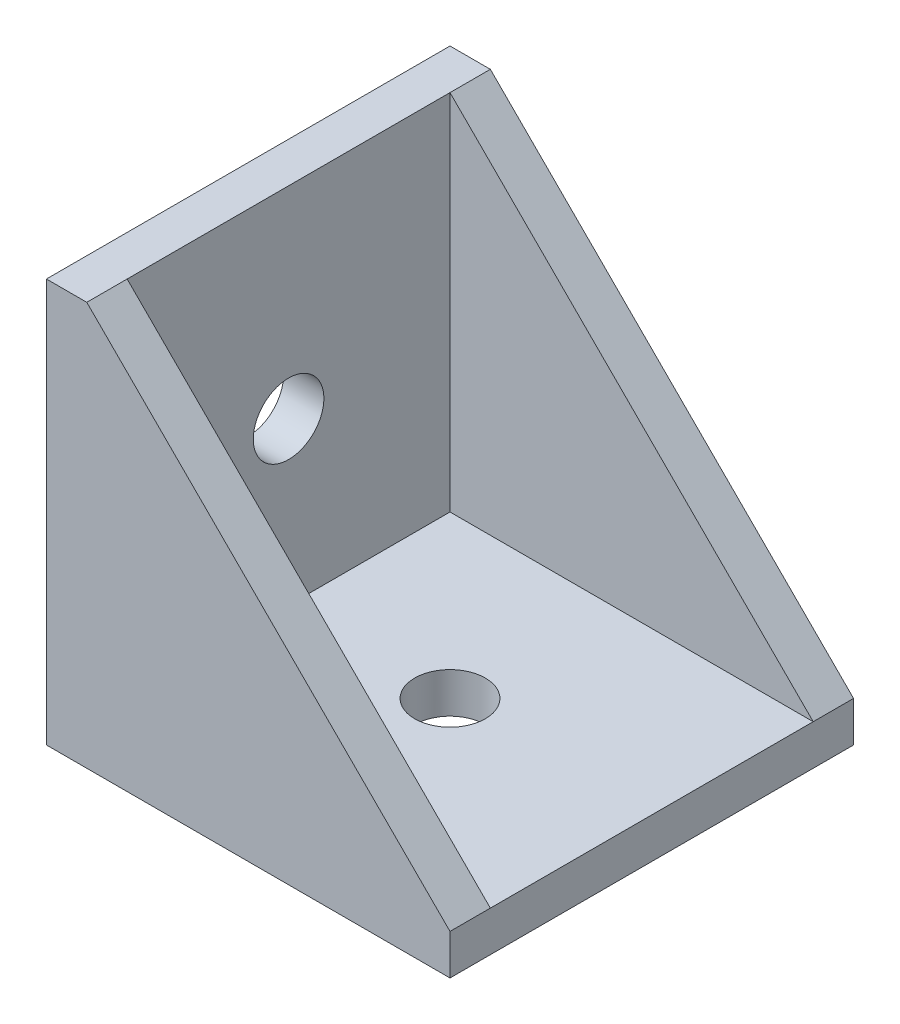
SolidWorks part; units mm, degrees
ref_plane "前视基准面" through (0, 0, 0) normal (0, 0, 1) x (1, 0, 0)
ref_plane "上视基准面" through (0, 0, 0) normal (0, 1, 0) x (1, 0, 0)
ref_plane "右视基准面" through (0, 0, 0) normal (1, 0, 0) x (0, 0, -1)
other "Configuration Table"
sketch "草图1" plane through (0, 0, 0) normal (0, 0, 1) x (1, 0, 0)
  line L0 (2, 20) -> (20, 2)
  line L1 (0, 0) -> (20, 0)
  line L2 (0, 0) -> (0, 20)
  line L3 (0, 20) -> (2, 20)
  line L4 (20, 0) -> (20, 2)
  dimension "D1" = 20
  dimension "D2" = 20
  dimension "D3" = 2
  dimension "D4" = 2
extrude "凸台-拉伸1" add sketch "草图1" along normal blind 20
sketch "草图2" plane through (0, 20, 0) normal (0, 1, 0) x (1, 0, 0)
  line L0 (2, -20) -> (2, 0) construction
  line L1 (2, -2) -> (20, -2)
  line L2 (2, -2) -> (2, -18)
  line L3 (2, -18) -> (20, -18)
  line L4 (20, -2) -> (20, -18)
  line L5 (20, -20) -> (20, 0) construction
  line L6 (20, 0) -> (2, 0) construction
  line L7 (20, -20) -> (2, -20) construction
  dimension "D1" = 2
  dimension "D2" = 18
  dimension "D3" = 2
extrude "切除-拉伸1" cut sketch "草图2" against normal blind 18
sketch "草图3" plane through (0, 0, 0) normal (0, -1, 0) x (1, 0, 0)
  line L0 (10, 20) -> (10, 10) construction
  line L1 (0, 20) -> (20, 20) construction
  circle A0 centre (10, 10) radius 1.75
  dimension "D1" = 3.5
extrude "切除-拉伸2" cut sketch "草图3" against normal blind 18
sketch "草图4" plane through (0, 0, 0) normal (-1, 0, 0) x (0, 0, 1)
  line L0 (-1000, 10) -> (10, 10) construction
  line L1 (0, 20) -> (0, 0) construction
  line L2 (20, 20) -> (20, 0) construction
  line L3 (10, 20) -> (10, 10) construction
  line L4 (20, 20) -> (0, 20) construction
  circle A0 centre (10, 10) radius 1.75
  point P4 (0, 10)
  point P7 (20, 10)
  point P12 (10, 20)
  dimension "D1" = 3.5
extrude "切除-拉伸3" cut sketch "草图4" against normal blind 18
